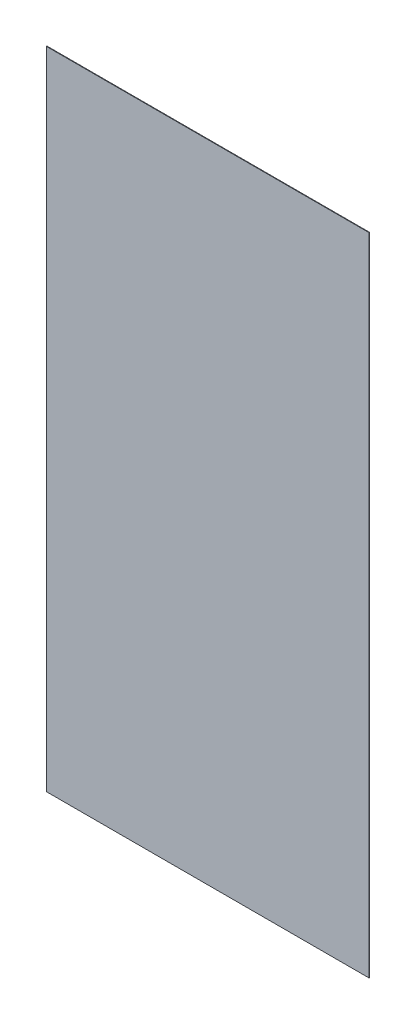
SolidWorks part; units mm, degrees
ref_plane "Front Plane" through (0, 0, 0) normal (0, 0, 1) x (1, 0, 0)
ref_plane "Top Plane" through (0, 0, 0) normal (0, 1, 0) x (1, 0, 0)
ref_plane "Right Plane" through (0, 0, 0) normal (1, 0, 0) x (0, 0, -1)
sketch "Sketch1" plane through (0, 0, 0) normal (0, 0, 1) x (1, 0, 0)
  line L1 (0, 0) -> (914.4, 0)
  line L2 (0, 0) -> (0, 1828.8)
  line L3 (0, 1828.8) -> (914.4, 1828.8)
  line L4 (914.4, 0) -> (914.4, 1828.8)
  dimension "D1" = 914.4
  dimension "D2" = 1828.8
extrude "Boss-Extrude1" add sketch "Sketch1" along normal blind 1.5875
